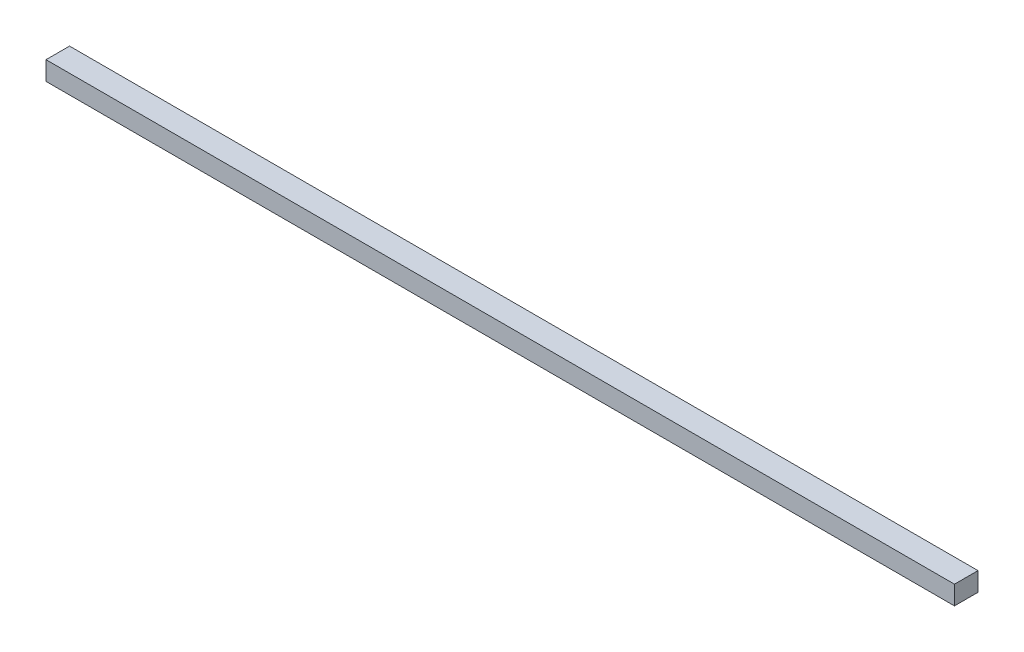
SolidWorks part; units mm, degrees
material "Teak"
ref_plane "Front Plane" through (0, 0, 0) normal (0, 0, 1) x (1, 0, 0)
ref_plane "Top Plane" through (0, 0, 0) normal (0, 1, 0) x (1, 0, 0)
ref_plane "Right Plane" through (0, 0, 0) normal (1, 0, 0) x (0, 0, -1)
sketch "Sketch1" plane through (0, 0, 0) normal (0, 0, 1) x (1, 0, 0)
  line L1 (965, -20) -> (-965, -20)
  line L2 (965, -20) -> (965, 20)
  line L3 (965, 20) -> (-965, 20)
  line L4 (-965, -20) -> (-965, 20)
  line L5 (965, -20) -> (-965, 20) construction
  line L6 (965, 20) -> (-965, -20) construction
  point P0 (0, 0)
  dimension "D1" = 1930
  dimension "D2" = 40
extrude "Boss-Extrude1" add sketch "Sketch1" along normal blind 50
